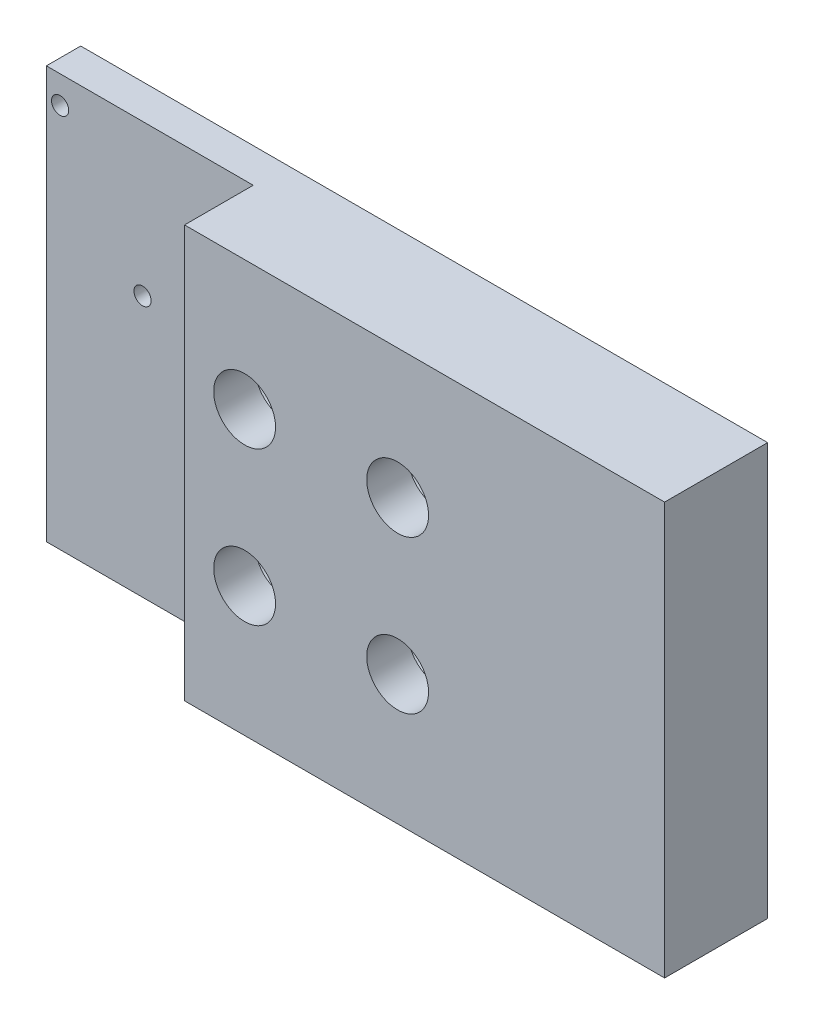
SolidWorks part; units mm, degrees
ref_plane "정면" through (0, 0, 0) normal (0, 0, 1) x (1, 0, 0)
ref_plane "윗면" through (0, 0, 0) normal (0, 1, 0) x (1, 0, 0)
ref_plane "우측면" through (0, 0, 0) normal (1, 0, 0) x (0, 0, -1)
sketch "스케치1" plane through (0, 0, 0) normal (0, 0, 1) x (1, 0, 0)
  line L1 (-50, 30) -> (50, 30)
  line L2 (-50, 30) -> (-50, -30)
  line L3 (-50, -30) -> (50, -30)
  line L4 (50, 30) -> (50, -30)
  line L5 (0, -30) -> (0, 30) construction
  line L6 (-50, 0) -> (50, 0) construction
  point P0 (0, 0)
  dimension "D1" = 100
  dimension "D2" = 60
extrude "보스-돌출1" add sketch "스케치1" along normal blind 15
sketch "스케치2" plane through (0, 0, 15) normal (0, 0, 1) x (1, 0, 0)
  line L0 (0, 30) -> (0, -30) construction
  line L1 (50, 30) -> (-50, 30) construction
  line L2 (-50, -30) -> (50, -30) construction
  line L3 (-50, 0) -> (50, 0) construction
  line L4 (-50, 30) -> (-50, -30) construction
  line L5 (50, -30) -> (50, 30) construction
  line L6 (-11.1369, 11.1369) -> (11.1369, -11.1369)
  line L7 (11.1369, 11.1369) -> (-11.1369, -11.1369)
  circle A0 centre (0, 0) radius 15.75
  point P14 (0, 0)
  dimension "D2" = 31.5
  dimension "D1" = 45
hole_wizard "Ø9.0 (9) 지름 구멍1" positions "3D스케치1" profile "스케치3" hole size "Ø9.0" standard "KS"
sketch3d "3D스케치1"
  point P0 (-11.1369, 11.1369, 15)
  point P3 (11.1369, 11.1369, 15)
  point P6 (-11.1369, -11.1369, 15)
  point P9 (11.1369, -11.1369, 15)
sketch "스케치3" plane through (-11.1369, 11.1369, 15) normal (1, 0, 0) x (0, -1, 0)
  line L0 (0, 0) -> (0, 8.7039)
  line L1 (0, 8.7039) -> (4.5, 6)
  line L2 (4.5, 6) -> (4.5, 0)
  line L5 (4.5, 0) -> (0, 0)
  line L10 (0, 8.7039) -> (-4.5, 6) construction
  line L11 (0, -6.35) -> (0, 107.95) construction
  dimension "구멍 지름" = 9
  dimension "구멍 깊이" = 6
  dimension "드릴 각도" = 118
hole_wizard "M5 나사 구멍2" positions "스케치7" profile "스케치6" tap size "M5" standard "KS" end condition through all
sketch "스케치7" plane through (0, 0, 15) normal (0, 0, 1) x (1, 0, 0)
  point P0 (-11.1369, 11.1369)
  point P3 (11.1369, 11.1369)
  point P6 (11.1369, -11.1369)
  point P9 (-11.1369, -11.1369)
sketch "스케치6" plane through (-11.1369, 11.1369, 15) normal (1, 0, 0) x (0, -1, 0)
  line L0 (0, 0) -> (0, 15)
  line L1 (0, 15) -> (2.1, 15)
  line L2 (2.1, 15) -> (2.1, 0)
  line L5 (2.1, 0) -> (0, 0)
  line L11 (0, -6.35) -> (0, 107.95) construction
  dimension "관통 탭 드릴 지름" = 4.2
  dimension "관통 탭 드릴 깊이" = 15
cosmetic thread "구멍 나사산7" parameters "D2"=5
cosmetic thread "구멍 나사산8" parameters "D2"=5
cosmetic thread "구멍 나사산9" parameters "D2"=5
cosmetic thread "구멍 나사산10" parameters "D2"=5
sketch "스케치8" plane through (0, 0, 15) normal (0, 0, 1) x (1, 0, 0)
  line L0 (-19.8844, 30) -> (-19.8844, -30)
  line L1 (50, 30) -> (-50, 30) construction
  line L2 (-50, -30) -> (50, -30) construction
  line L3 (-50, 30) -> (-50, -30) construction
  line L4 (-19.8844, 30) -> (-50, 30)
  line L5 (-50, 30) -> (-50, -30)
  line L6 (-50, -30) -> (-19.8844, -30)
  dimension "D1" = 30.1156
extrude "컷-돌출2" cut sketch "스케치8" against normal blind 10
sketch "스케치12" plane through (0, 0, 0) normal (0, 0, -1) x (-1, 0, 0)
  line L0 (19.8844, 30) -> (50, 30) construction
  line L1 (50, 30) -> (50, -30) construction
  point P0 (48, 26)
  point P6 (36, 8)
  dimension "D1" = 4
  dimension "D2" = 2
  dimension "D3" = 12
  dimension "D4" = 18
hole_wizard "M3 나사 구멍1" positions "3D스케치3" profile "스케치13" tap size "M3" standard "KS" end condition through all
sketch3d "3D스케치3"
  point P0 (-36, 8, 0)
  point P3 (-48, 26, 0)
sketch "스케치13" plane through (-36, 8, 0) normal (1, 0, 0) x (0, 1, 0)
  line L0 (0, 0) -> (0, 15)
  line L1 (0, 15) -> (1.25, 15)
  line L2 (1.25, 15) -> (1.25, 0)
  line L5 (1.25, 0) -> (0, 0)
  line L11 (0, -6.35) -> (0, 107.95) construction
  dimension "관통 탭 드릴 지름" = 2.5
  dimension "관통 탭 드릴 깊이" = 15
cosmetic thread "구멍 나사산11" parameters "D2"=3
cosmetic thread "구멍 나사산12" parameters "D2"=3
